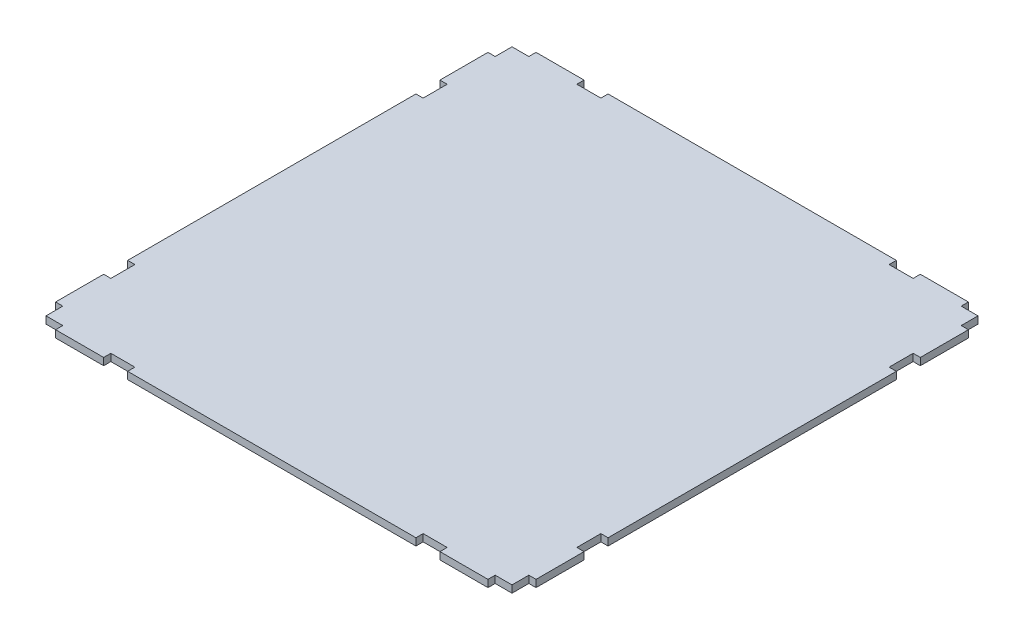
SolidWorks part; units mm, degrees
ref_plane "Alzado" through (0, 0, 0) normal (0, 0, 1) x (1, 0, 0)
ref_plane "Planta" through (0, 0, 0) normal (0, 1, 0) x (1, 0, 0)
ref_plane "Vista lateral" through (0, 0, 0) normal (1, 0, 0) x (0, 0, -1)
sketch "Sketch1" plane through (0, 0, 0) normal (0, 1, 0) x (1, 0, 0)
  line L0 (-100, 60) -> (-100, -60)
  line L1 (-90, 100) -> (-70, 100)
  line L2 (-100, 90) -> (-100, 70)
  line L3 (-90, -100) -> (-70, -100)
  line L4 (100, 90) -> (100, 70)
  line L5 (0, 0) -> (0, 70) construction
  line L6 (97, 70) -> (100, 70)
  line L7 (-90, 100) -> (-90, 97)
  line L8 (-70, 97) -> (-60, 97)
  line L9 (-70, 97) -> (-70, 100)
  line L10 (-100, 90) -> (-97, 90)
  line L11 (-60, 97) -> (-60, 100)
  line L12 (-97, 70) -> (-100, 70)
  line L13 (-97, 90) -> (-97, 97)
  line L14 (-90, 97) -> (-97, 97)
  line L15 (-97, 70) -> (-97, 60)
  line L16 (-97, 60) -> (-100, 60)
  line L17 (-60, 100) -> (60, 100)
  line L18 (97, 60) -> (100, 60)
  line L19 (97, 70) -> (97, 60)
  line L21 (100, 90) -> (97, 90)
  line L22 (97, 90) -> (97, 97)
  line L23 (90, 97) -> (97, 97)
  line L24 (90, 100) -> (90, 97)
  line L25 (90, 100) -> (70, 100)
  line L26 (70, 97) -> (70, 100)
  line L27 (60, 97) -> (60, 100)
  line L28 (70, 97) -> (60, 97)
  line L29 (0, 0) -> (36.3288, 0) construction
  line L30 (97, -60) -> (100, -60)
  line L31 (97, -70) -> (97, -60)
  line L32 (97, -70) -> (100, -70)
  line L33 (100, -90) -> (97, -90)
  line L34 (97, -90) -> (97, -97)
  line L35 (90, -97) -> (97, -97)
  line L36 (90, -100) -> (90, -97)
  line L37 (70, -97) -> (70, -100)
  line L38 (60, -97) -> (60, -100)
  line L39 (70, -97) -> (60, -97)
  line L40 (-60, -97) -> (-60, -100)
  line L41 (-70, -97) -> (-60, -97)
  line L42 (-70, -97) -> (-70, -100)
  line L43 (-90, -100) -> (-90, -97)
  line L44 (-90, -97) -> (-97, -97)
  line L45 (-97, -90) -> (-97, -97)
  line L46 (-100, -90) -> (-97, -90)
  line L47 (-97, -70) -> (-100, -70)
  line L48 (-97, -60) -> (-100, -60)
  line L49 (-97, -70) -> (-97, -60)
  line L51 (100, 60) -> (100, -60)
  line L52 (100, -70) -> (100, -90)
  line L53 (70, -100) -> (90, -100)
  line L54 (-60, -100) -> (60, -100)
  line L55 (-100, -70) -> (-100, -90)
  point P0 (0, 0)
  dimension "D4" = 20
  dimension "D5" = 3
  dimension "D7" = 20
  dimension "D8" = 3
  dimension "D9" = 10
  dimension "D10" = 10
extrude "Boss-Extrude1" add sketch "Sketch1" along normal blind 3
